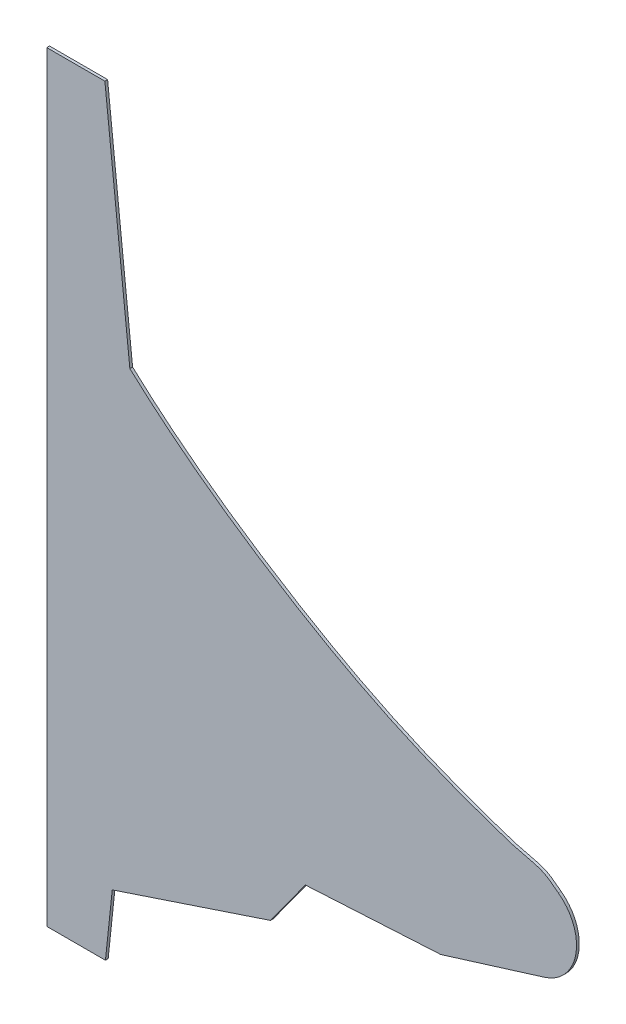
SolidWorks part; units mm, degrees
ref_plane "Piano frontale" through (0, 0, 0) normal (0, 0, 1) x (1, 0, 0)
ref_plane "Piano superiore" through (0, 0, 0) normal (0, 1, 0) x (1, 0, 0)
ref_plane "Piano destro" through (0, 0, 0) normal (1, 0, 0) x (0, 0, -1)
sketch "Schizzo1" plane through (0, 0, 0) normal (0, 0, 1) x (1, 0, 0)
  line L0 (10.3654, 74.8314) -> (10.3654, 10.7767)
  line L1 (10.3654, 74.8314) -> (15.2563, 74.8314)
  line L2 (15.2563, 74.8314) -> (17.3592, 54.9271)
  line L3 (10.3654, 10.7767) -> (15.303, 10.7767)
  line L4 (15.303, 10.7767) -> (15.8765, 16.1952)
  line L5 (15.8765, 16.1952) -> (29.1952, 20.6267)
  line L6 (29.1952, 20.6267) -> (32.1311, 24.6762)
  line L7 (32.1311, 24.6762) -> (43.5207, 25.3065)
  line L8 (43.5207, 25.3065) -> (52.2515, 28.0124)
  arc A0 (52.2515, 28.0124) -> (53.4294, 34.7438) centre (51.1148, 31.6801) ccw
  spline S0 degree 3 poles (17.3592, 54.9271) (21.3758, 51.2209) (27.6184, 46.7463) (36.5344, 41.5778) (42.4656, 38.8113) (47.4534, 37.0341) (49.9312, 36.2003) (51.2837, 35.9179) (52.2697, 35.6131) (52.7083, 35.3233) (53.4294, 34.7438) knots 0 0 0 0 0.391005 0.55037 0.736981 0.86548 0.916488 0.943204 0.951555 1 1 1 1
extrude "Estrusione-Estrusione1" add sketch "Schizzo1" along normal blind 0.23
